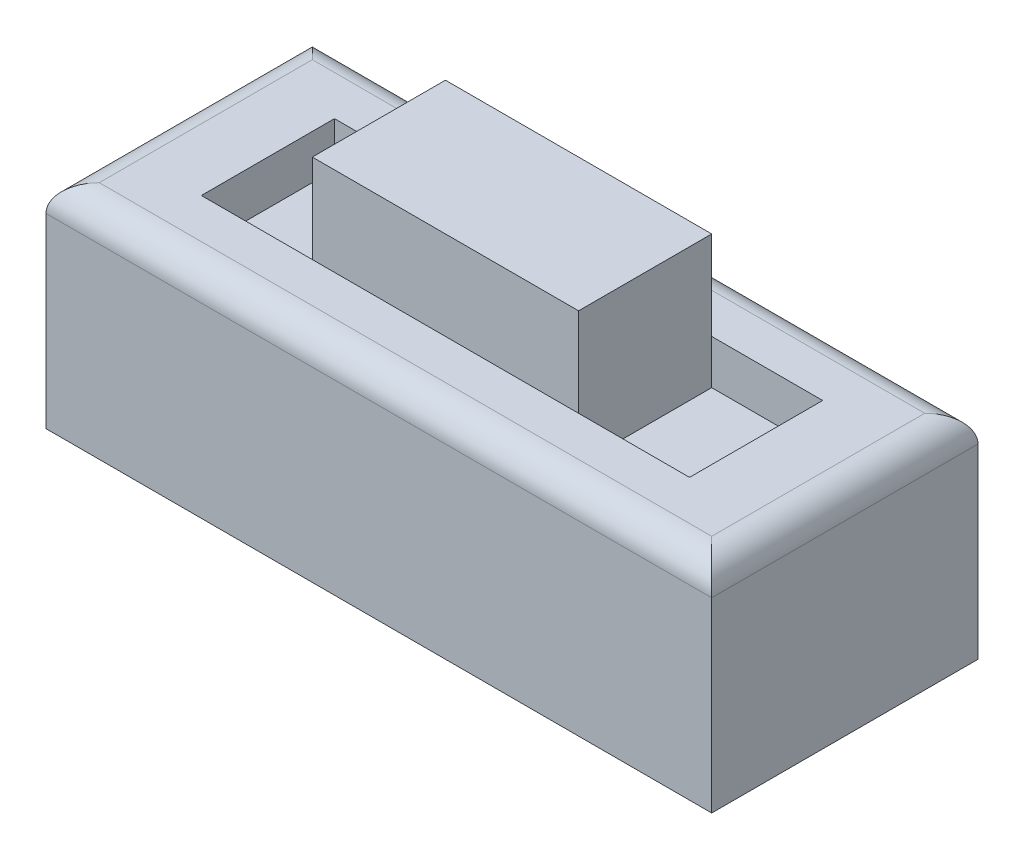
SolidWorks part; units mm, degrees
ref_plane "Front Plane" through (0, 0, 0) normal (0, 0, 1) x (1, 0, 0)
ref_plane "Top Plane" through (0, 0, 0) normal (0, 1, 0) x (1, 0, 0)
ref_plane "Right Plane" through (0, 0, 0) normal (1, 0, 0) x (0, 0, -1)
sketch "Sketch1" plane through (0, 0, 0) normal (0, 1, 0) x (1, 0, 0)
  line L1 (-4.1897, 2.6664) -> (3.3103, 2.6664)
  line L2 (-4.1897, 2.6664) -> (-4.1897, -0.3336)
  line L3 (-4.1897, -0.3336) -> (3.3103, -0.3336)
  line L4 (3.3103, 2.6664) -> (3.3103, -0.3336)
  dimension "D1" = 7.5
  dimension "D2" = 3
extrude "Boss-Extrude1" add sketch "Sketch1" along normal blind 2.4
sketch "Sketch2" plane through (0, 2.4, 0) normal (0, 1, 0) x (1, 0, 0)
  line L0 (3.3103, -0.3336) -> (3.3103, 2.6664) construction
  line L1 (-1.9397, 1.9164) -> (1.0603, 1.9164)
  line L2 (-1.9397, 1.9164) -> (-1.9397, 0.4164)
  line L3 (-1.9397, 0.4164) -> (1.0603, 0.4164)
  line L4 (1.0603, 1.9164) -> (1.0603, 0.4164)
  line L5 (-4.1897, -0.3336) -> (3.3103, -0.3336) construction
  dimension "D1" = 3
  dimension "D2" = 1.5
  dimension "D3" = 2.25
  dimension "D4" = 0.75
extrude "Boss-Extrude2" add sketch "Sketch2" along normal blind 1
sketch "Sketch3" plane through (0, 2.4, 0) normal (0, 1, 0) x (1, 0, 0)
  line L0 (1.0603, 0.4164) -> (1.0603, 1.9164) construction
  line L1 (2.3103, 1.9164) -> (1.0603, 1.9164)
  line L2 (2.3103, 1.9164) -> (2.3103, 0.4164)
  line L3 (2.3103, 0.4164) -> (1.0603, 0.4164)
  line L4 (1.0603, 1.9164) -> (1.0603, 0.4164)
  line L6 (-3.1897, 1.9164) -> (-1.9397, 1.9164)
  line L7 (-3.1897, 1.9164) -> (-3.1897, 0.4164)
  line L8 (-3.1897, 0.4164) -> (-1.9397, 0.4164)
  line L9 (-1.9397, 1.9164) -> (-1.9397, 0.4164)
  dimension "D1" = 1.25
  dimension "D2" = 1.25
extrude "Cut-Extrude1" cut sketch "Sketch3" against normal blind 0.5
sketch "Sketch4" plane through (0, 0, 0) normal (0, -1, 0) x (1, 0, 0)
  line L0 (3.3103, 0.3336) -> (3.3103, -2.6664) construction
  line L1 (1.8103, -0.7119) -> (2.3103, -0.7119)
  line L2 (1.8103, -0.7119) -> (1.8103, -1.7119)
  line L3 (1.8103, -1.7119) -> (2.3103, -1.7119)
  line L4 (2.3103, -0.7119) -> (2.3103, -1.7119)
  line L5 (-0.6897, -0.7119) -> (-0.6897, -1.7119)
  line L6 (-0.6897, -0.7119) -> (-0.1897, -0.7119)
  line L7 (-0.1897, -0.7119) -> (-0.1897, -1.7119)
  line L8 (-0.6897, -1.7119) -> (-0.1897, -1.7119)
  line L9 (-3.1897, -0.7119) -> (-3.1897, -1.7119)
  line L10 (-3.1897, -0.7119) -> (-2.6897, -0.7119)
  line L11 (-2.6897, -0.7119) -> (-2.6897, -1.7119)
  line L12 (-3.1897, -1.7119) -> (-2.6897, -1.7119)
  dimension "D1" = 0.5
  dimension "D2" = 1
  dimension "D3" = 1
  dimension "D4" = 3
extrude "Cut-Extrude2" cut sketch "Sketch4" against normal blind 1
fillet "Fillet1" radius 0.3 4 edges at (-4.1897, 2.4, -1.1664) (-0.4397, 2.4, -2.6664) (3.3103, 2.4, -1.1664) (-0.4397, 2.4, 0.3336)
